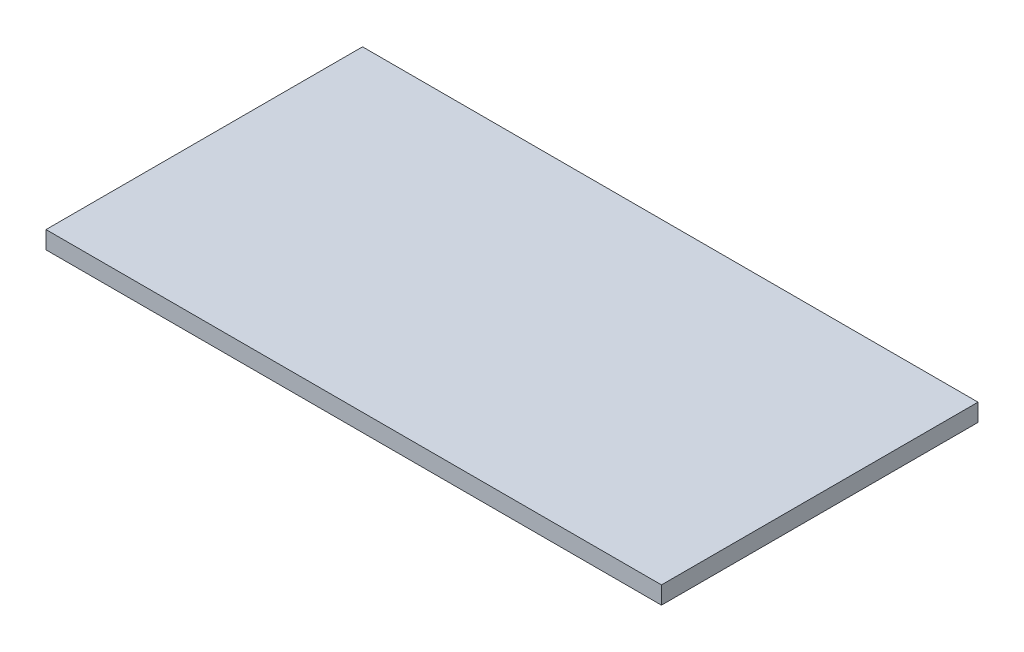
SolidWorks part; units mm, degrees
ref_plane "Front Plane" through (0, 0, 0) normal (0, 0, 1) x (1, 0, 0)
ref_plane "Top Plane" through (0, 0, 0) normal (0, 1, 0) x (1, 0, 0)
ref_plane "Right Plane" through (0, 0, 0) normal (1, 0, 0) x (0, 0, -1)
sketch "Sketch1" plane through (0, 0, 0) normal (0, 1, 0) x (1, 0, 0)
  line L1 (0, 0) -> (175, 0)
  line L2 (0, 0) -> (0, -90)
  line L3 (0, -90) -> (175, -90)
  line L4 (175, 0) -> (175, -90)
  dimension "D1" = 90
  dimension "D2" = 175
extrude "Boss-Extrude1" add sketch "Sketch1" along normal blind 5
sketch "Sketch3" plane through (0, 0, 0) normal (0, -1, 0) x (1, 0, 0)
  line L0 (0, 45) -> (192.4731, 45) construction
  line L1 (0, 0) -> (0, 90) construction
